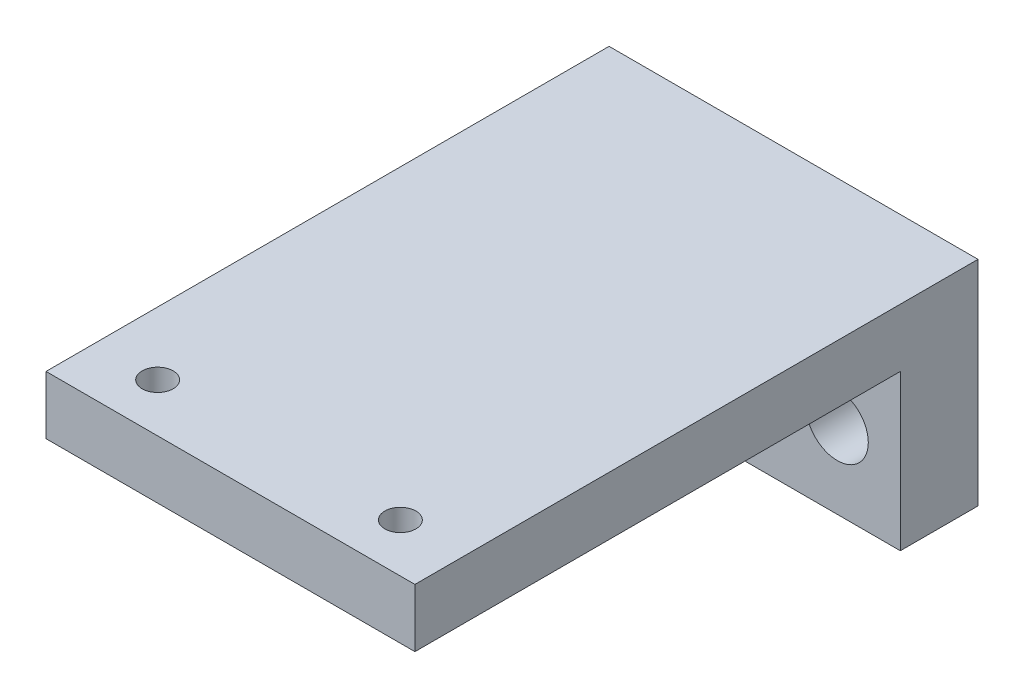
SolidWorks part; units mm, degrees
ref_plane "前视基准面" through (0, 0, 0) normal (0, 0, 1) x (1, 0, 0)
ref_plane "上视基准面" through (0, 0, 0) normal (0, 1, 0) x (1, 0, 0)
ref_plane "右视基准面" through (0, 0, 0) normal (1, 0, 0) x (0, 0, -1)
sketch "草图1" plane through (0, 0, 0) normal (0, 0, 1) x (1, 0, 0)
  line L1 (-19.3199, 32.4818) -> (18.6801, 32.4818)
  line L2 (-19.3199, 32.4818) -> (-19.3199, -5.5182)
  line L3 (-19.3199, -5.5182) -> (18.6801, -5.5182)
  line L4 (18.6801, 32.4818) -> (18.6801, -5.5182)
  dimension "D1" = 38
  dimension "D2" = 38
extrude "拉伸1" add sketch "草图1" along normal blind 8
sketch "草图2" plane through (0, 0, 8) normal (0, 0, 1) x (1, 0, 0)
  line L0 (18.6801, -5.5182) -> (18.6801, 32.4818) construction
  line L1 (-19.3199, 32.4818) -> (18.6801, 32.4818)
  line L2 (-19.3199, 32.4818) -> (-19.3199, 26.4818)
  line L3 (-19.3199, 26.4818) -> (18.6801, 26.4818)
  line L4 (18.6801, 32.4818) -> (18.6801, 26.4818)
  dimension "D1" = 6
extrude "拉伸2" add sketch "草图2" along normal blind 50
sketch "草图3" plane through (0, 0, 8) normal (0, 0, 1) x (1, 0, 0)
  line L0 (18.6801, -5.5182) -> (18.6801, 26.4818) construction
  line L1 (-19.3199, -5.5182) -> (18.6801, -5.5182)
  line L2 (-19.3199, -5.5182) -> (-19.3199, 10.4818)
  line L3 (-19.3199, 10.4818) -> (18.6801, 10.4818)
  line L4 (18.6801, -5.5182) -> (18.6801, 10.4818)
extrude "切除-拉伸1" cut sketch "草图3" against normal blind 10
sketch "草图4" plane through (0, 0, 8) normal (0, 0, 1) x (1, 0, 0)
  line L0 (-1019.3199, 18.4818) -> (48980.6801, 18.4818) construction
  line L1 (-19.3199, 26.4818) -> (-19.3199, 10.4818) construction
  line L2 (-12.8199, -981.5182) -> (-12.8199, 49018.4818) construction
  line L3 (12.1801, -981.5182) -> (12.1801, 49018.4818) construction
  line L5 (-0.3199, -967.5182) -> (-0.3199, 49032.4818) construction
  line L6 (18.6801, 32.4818) -> (-19.3199, 32.4818) construction
  circle A0 centre (-12.8199, 18.4818) radius 3.2
  circle A1 centre (12.1801, 18.4818) radius 3.2
  point P5 (-19.3199, 18.4818)
  point P18 (-0.3199, 32.4818)
  dimension "D3" = 6.4
  dimension "D1" = 25
  dimension "D2" = 12.5
extrude "切除-拉伸2" cut sketch "草图4" against normal blind 10
sketch "草图5" plane through (0, 26.4818, 0) normal (0, -1, 0) x (1, 0, 0)
  line L0 (-19.3199, 58) -> (18.6801, 58) construction
  line L1 (-0.3199, -942) -> (-0.3199, 49058) construction
  circle A0 centre (12.1801, 53) radius 1.6
  circle A1 centre (-12.8199, 53) radius 1.6
  point P9 (-0.3199, 58)
  dimension "D3" = 3.2
  dimension "D5" = 3.2
  dimension "D1" = 25
  dimension "D2" = 5
  dimension "D4" = 12.5
extrude "切除-拉伸3" cut sketch "草图5" against normal blind 10
